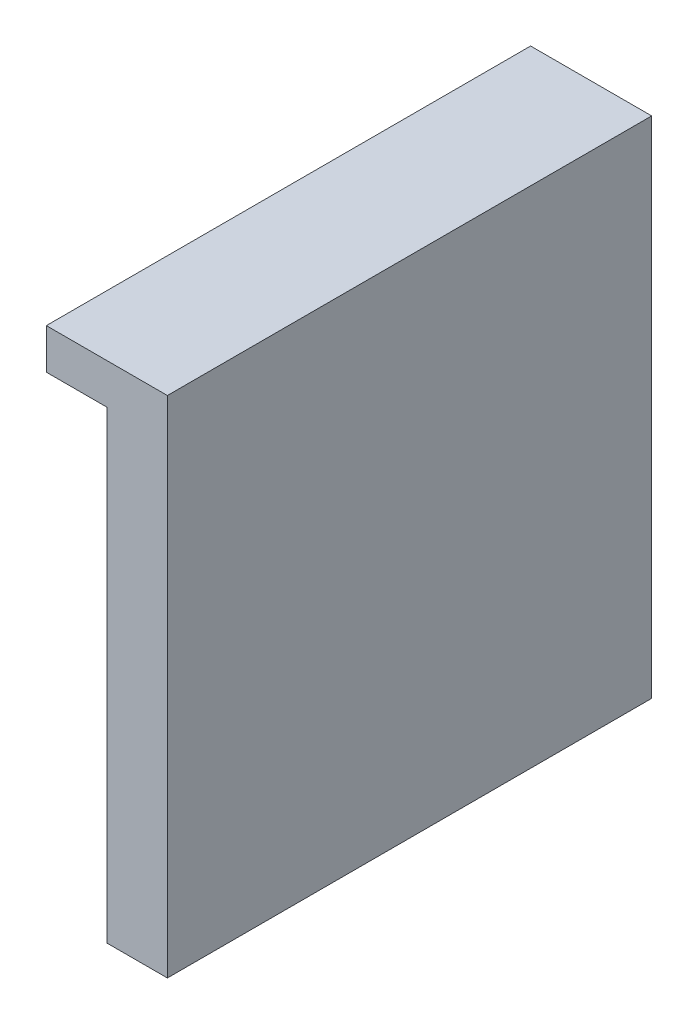
SolidWorks part; units mm, degrees
ref_plane "Front Plane" through (0, 0, 0) normal (0, 0, 1) x (1, 0, 0)
ref_plane "Top Plane" through (0, 0, 0) normal (0, 1, 0) x (1, 0, 0)
ref_plane "Right Plane" through (0, 0, 0) normal (1, 0, 0) x (0, 0, -1)
sketch "Sketch1" plane through (0, 0, 0) normal (0, 1, 0) x (1, 0, 0)
  line L1 (0, 0) -> (3, 0)
  line L2 (0, 0) -> (0, 24)
  line L3 (0, 24) -> (3, 24)
  line L4 (3, 0) -> (3, 24)
  dimension "D1" = 3
  dimension "D2" = 24
extrude "Boss-Extrude1" add sketch "Sketch1" along normal blind 23 contours L2 L1 L4 L3
sketch "Sketch2" plane through (0, 23, 0) normal (0, 1, 0) x (1, 0, 0)
  line L0 (0, 24) -> (3, 24) construction
  line L1 (3, 0) -> (-3, 0)
  line L2 (3, 0) -> (3, 24)
  line L3 (3, 24) -> (-3, 24)
  line L4 (-3, 0) -> (-3, 24)
  dimension "D1" = 6
extrude "Boss-Extrude2" add sketch "Sketch2" along normal blind 2 contours L2 L1 L4 L3
sketch "Sketch3" plane through (0, 0, 0) normal (-1, 0, 0) x (0, 0, 1)
  line L0 (0, 23) -> (-24, 23) construction
  line L1 (-23, 12) -> (-1, 12)
  line L2 (-23, 12) -> (-23, 21)
  line L3 (-23, 21) -> (-1, 21)
  line L4 (-1, 12) -> (-1, 21)
  line L5 (0, 23) -> (0, 0) construction
  line L6 (-24, 23) -> (-24, 0) construction
  dimension "D1" = 2
  dimension "D2" = 1
  dimension "D3" = 1
  dimension "D4" = 9
extrude "Cut-Extrude1" cut sketch "Sketch3" against normal blind 1
